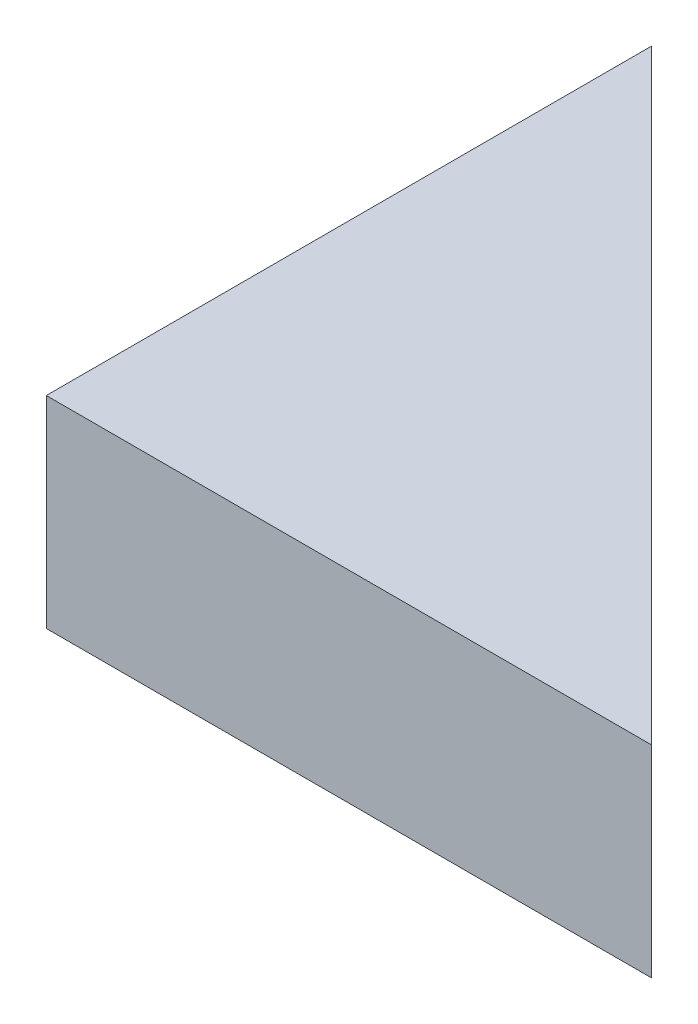
SolidWorks part; units mm, degrees
ref_plane "Front Plane" through (0, 0, 0) normal (0, 0, 1) x (1, 0, 0)
ref_plane "Top Plane" through (0, 0, 0) normal (0, 1, 0) x (1, 0, 0)
ref_plane "Right Plane" through (0, 0, 0) normal (1, 0, 0) x (0, 0, -1)
sketch "Sketch1" plane through (0, 0, 0) normal (0, 1, 0) x (1, 0, 0)
  line L0 (57.3934, -1069.2039) -> (19.2934, -1069.2039)
  line L1 (6.5934, -1069.2039) -> (779.2366, -1069.2039) construction
  line L2 (19.2934, -1069.2039) -> (19.2934, -1031.1039)
  line L3 (19.2934, -481.8289) -> (19.2934, -1069.2039) construction
  line L4 (19.2934, -1031.1039) -> (57.3934, -1069.2039)
  dimension "D1" = 38.1
extrude "Boss-Extrude1" add sketch "Sketch1" against normal blind 12.7
equation "\"CORNER_SIDE_LENGTH\"=1.5"
equation "\"D1@Sketch1\"=\"CORNER_SIDE_LENGTH\""
equation "\"WOOD_THICKNESS\"=0.5"
equation "\"D1@Boss-Extrude1\"=\"WOOD_THICKNESS\""
